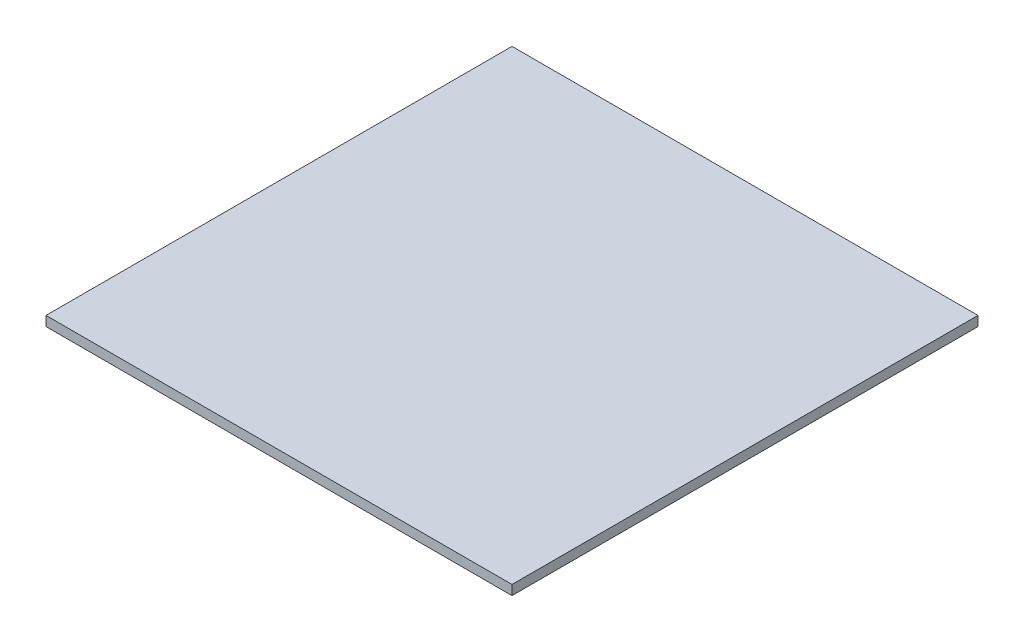
SolidWorks part; units mm, degrees
ref_plane "Front Plane" through (0, 0, 0) normal (0, 0, 1) x (1, 0, 0)
ref_plane "Top Plane" through (0, 0, 0) normal (0, 1, 0) x (1, 0, 0)
ref_plane "Right Plane" through (0, 0, 0) normal (1, 0, 0) x (0, 0, -1)
sketch "Sketch1" plane through (0, 0, 0) normal (0, 1, 0) x (1, 0, 0)
  line L1 (-438.9437, -438.9437) -> (438.9438, -438.9437)
  line L2 (-438.9437, -438.9437) -> (-438.9437, 438.9438)
  line L3 (-438.9437, 438.9438) -> (438.9438, 438.9438)
  line L4 (438.9438, -438.9437) -> (438.9438, 438.9438)
  line L5 (-438.9437, -438.9437) -> (438.9438, 438.9438) construction
  line L6 (-438.9437, 438.9438) -> (438.9438, -438.9437) construction
  point P0 (0, 0)
  dimension "D1" = 877.8875
  dimension "D2" = 877.8875
extrude "Boss-Extrude1" add sketch "Sketch1" along normal blind 18.2562
